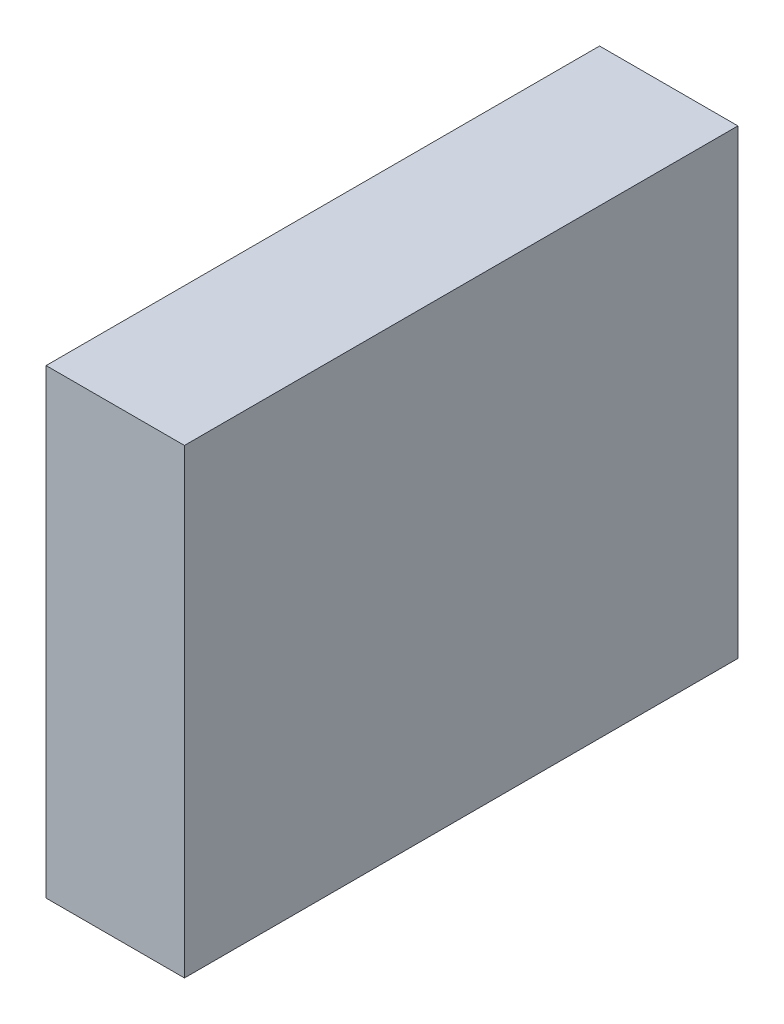
SolidWorks part; units mm, degrees
ref_plane "Front Plane" through (0, 0, 0) normal (0, 0, 1) x (1, 0, 0)
ref_plane "Top Plane" through (0, 0, 0) normal (0, 1, 0) x (1, 0, 0)
ref_plane "Right Plane" through (0, 0, 0) normal (1, 0, 0) x (0, 0, -1)
sketch "Sketch1" plane through (0, 0, 0) normal (0, 0, 1) x (1, 0, 0)
  line L1 (76.2, -254) -> (-76.2, -254)
  line L2 (76.2, -254) -> (76.2, 254)
  line L3 (76.2, 254) -> (-76.2, 254)
  line L4 (-76.2, -254) -> (-76.2, 254)
  line L5 (76.2, -254) -> (-76.2, 254) construction
  line L6 (76.2, 254) -> (-76.2, -254) construction
  point P0 (0, 0)
  dimension "D1" = 152.4
  dimension "D2" = 508
extrude "Boss-Extrude1" add sketch "Sketch1" along normal blind 609.6
